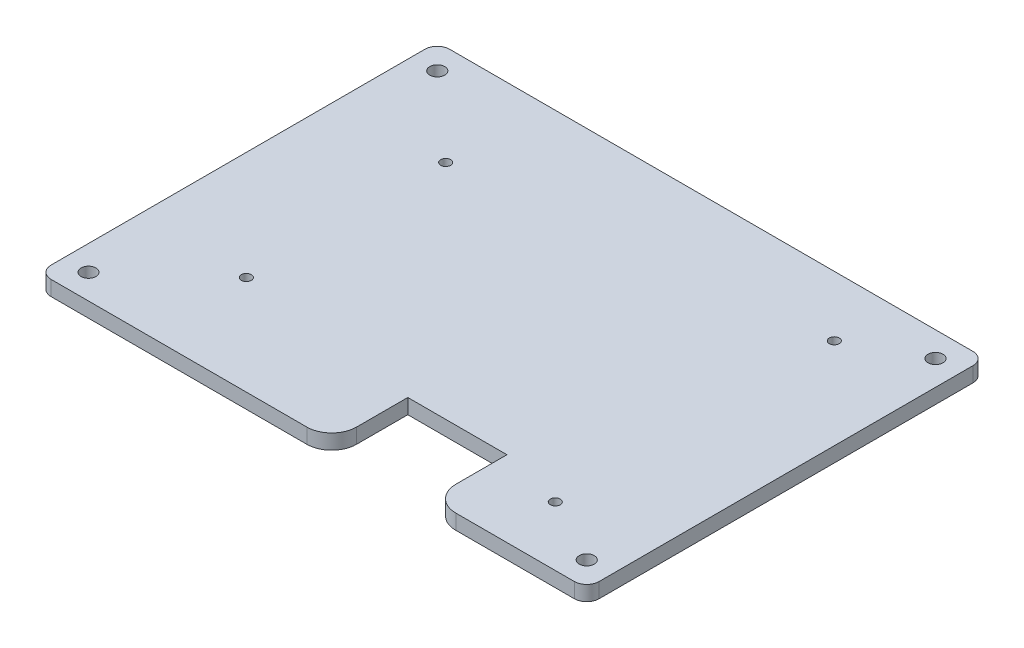
SolidWorks part; units mm, degrees
material "MDF"
ref_plane "Front Plane" through (0, 0, 0) normal (0, 0, 1) x (1, 0, 0)
ref_plane "Top Plane" through (0, 0, 0) normal (0, 1, 0) x (1, 0, 0)
ref_plane "Right Plane" through (0, 0, 0) normal (1, 0, 0) x (0, 0, -1)
sketch "Sketch5" plane through (0, 0, 0) normal (0, 1, 0) x (1, 0, 0)
  line L1 (0, 0) -> (110, 0)
  line L2 (0, 0) -> (0, 80)
  line L3 (0, 80) -> (110, 80)
  line L4 (110, 0) -> (110, 80)
  circle A0 centre (91.7649, 67.9208) radius 1
  circle A1 centre (21.7649, 59.9208) radius 1
  circle A2 centre (21.7649, 19.9208) radius 1
  circle A3 centre (91.7649, 11.9208) radius 1
  dimension "D1" = 2
  dimension "D2" = 21.7649
  dimension "D3" = 91.7649
  dimension "D4" = 110
  dimension "D5" = 11.9208
  dimension "D6" = 19.9208
  dimension "D7" = 59.9208
  dimension "D8" = 67.9208
  dimension "D9" = 80
extrude "Boss-Extrude1" add sketch "Sketch5" along normal blind 3
sketch "Sketch6" plane through (0, 3, 0) normal (0, 1, 0) x (1, 0, 0)
  line L0 (110, 80) -> (0, 80) construction
  line L2 (0, 80) -> (0, 0) construction
  line L3 (110, 0) -> (110, 80) construction
  line L4 (0, 0) -> (110, 0) construction
  circle A0 centre (5, 75) radius 1.5
  circle A1 centre (105, 75) radius 1.5
  circle A2 centre (105, 5) radius 1.5
  circle A3 centre (5, 5) radius 1.5
  dimension "D1" = 5
  dimension "D5" = 3
  dimension "D2" = 5
  dimension "D3" = 5
  dimension "D4" = 5
extrude "Cut-Extrude1" cut sketch "Sketch6" against normal through all
fillet "Fillet1" radius 2.5 4 edges at (110, 1.5, -80) (110, 1.5, 0) (0, 1.5, 0) (0, 1.5, -80)
sketch "Sketch7" plane through (0, 3, 0) normal (0, 1, 0) x (1, 0, 0)
  line L0 (58.8149, 15.2708) -> (58.8149, 0)
  line L1 (2.5, 0) -> (107.5, 0) construction
  line L2 (78.7149, 0) -> (78.7149, 15.2708)
  line L3 (78.7149, 15.2708) -> (58.8149, 15.2708)
  line L4 (110, 2.5) -> (110, 77.5) construction
  dimension "D1" = 31.2851
  dimension "D2" = 51.1851
  dimension "D3" = 64.7292
extrude "Cut-Extrude2" cut sketch "Sketch7" against normal blind 6
fillet "Fillet2" radius 5 2 edges at (78.7149, 1.5, 0) (58.8149, 1.5, 0)
